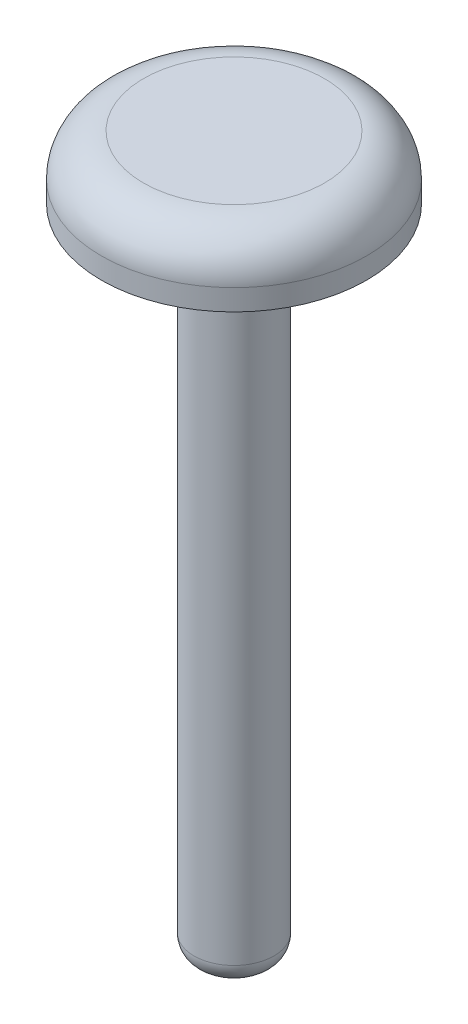
SolidWorks part; units mm, degrees
ref_plane "Alzado" through (0, 0, 0) normal (0, 0, 1) x (1, 0, 0)
ref_plane "Planta" through (0, 0, 0) normal (0, 1, 0) x (1, 0, 0)
ref_plane "Vista lateral" through (0, 0, 0) normal (1, 0, 0) x (0, 0, -1)
sketch "Croquis1" plane through (0, 0, 0) normal (0, 1, 0) x (1, 0, 0)
  circle A0 centre (0, 0) radius 0.95
extrude "Saliente-Extruir1" add sketch "Croquis1" along normal blind 17
sketch "Croquis2" plane through (0, 17, 0) normal (0, 1, 0) x (1, 0, 0)
  circle A0 centre (0, 0) radius 3.15
extrude "Saliente-Extruir2" add sketch "Croquis2" along normal blind 0.0001 and the other way blind 1.5
fillet "Redondeo3" radius 0.5 1 edges at (0, 0, 0.95)
fillet "Redondeo5" radius 1 1 edges at (0, 17.0001, 3.15)
sketch "Croquis4" plane through (0, 15.5, 0) normal (0, -1, 0) x (-1, 0, 0)
  circle A1 centre (0, 0) radius 2.65
  circle M2 centre (0, 0) radius 0.95
extrude "Cortar-Extruir4" cut sketch "Croquis4" against normal blind 1 contours A1 M2
